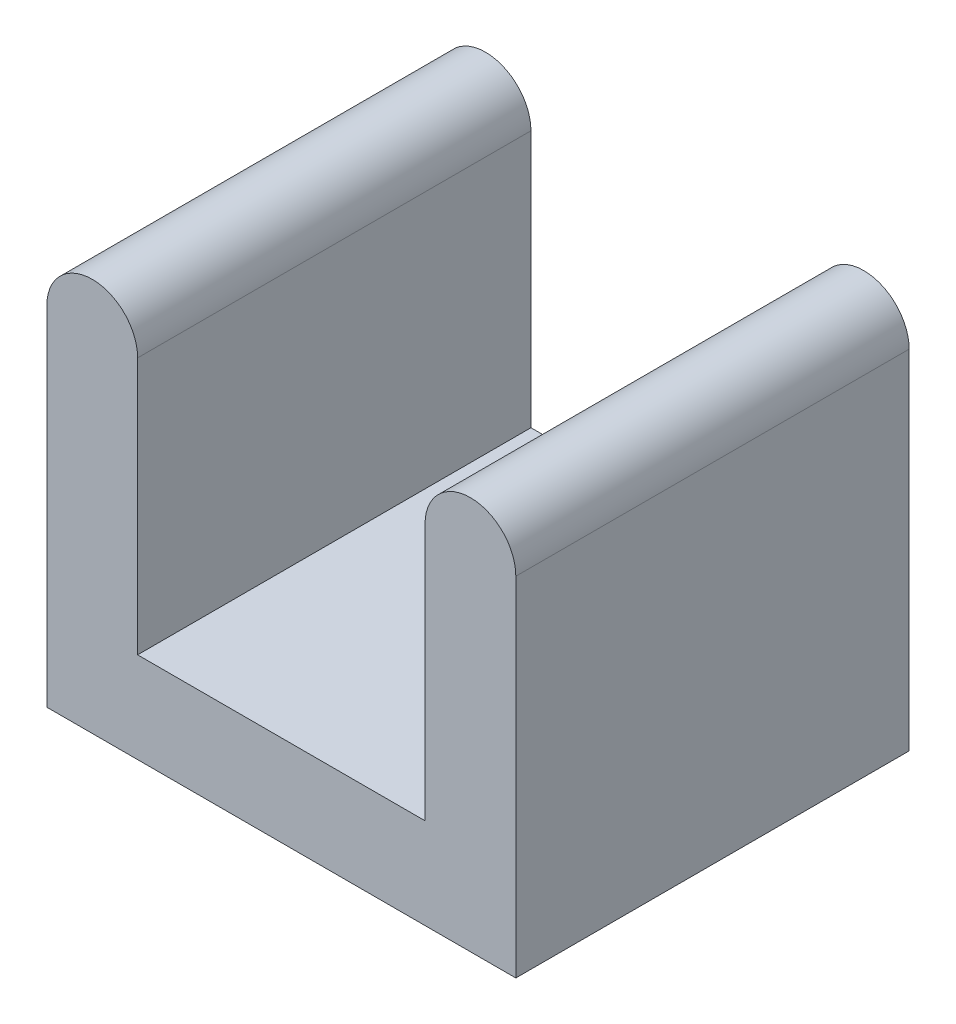
SolidWorks part; units mm, degrees
ref_plane "Front Plane" through (0, 0, 0) normal (0, 0, 1) x (1, 0, 0)
ref_plane "Top Plane" through (0, 0, 0) normal (0, 1, 0) x (1, 0, 0)
ref_plane "Right Plane" through (0, 0, 0) normal (1, 0, 0) x (0, 0, -1)
sketch "Sketch2" plane through (0, 0, 0) normal (0, 0, 1) x (1, 0, 0)
  line L0 (-29.0441, 29.9265) -> (-29.0441, 9.9265)
  line L1 (-29.0441, 9.9265) -> (-4.0441, 9.9265)
  line L2 (-4.0441, 9.9265) -> (-4.0441, 29.9265)
  line L3 (-32.0441, 29.9265) -> (-32.0441, 6.9265)
  line L4 (-32.0441, 6.9265) -> (-1.0441, 6.9265)
  line L5 (-1.0441, 6.9265) -> (-1.0441, 29.9265)
  line L6 (-26.0441, 29.9265) -> (-26.0441, 12.9265)
  line L7 (-26.0441, 12.9265) -> (-7.0441, 12.9265)
  line L8 (-7.0441, 12.9265) -> (-7.0441, 29.9265)
  arc A0 (-32.0441, 29.9265) -> (-26.0441, 29.9265) centre (-29.0441, 29.9265) cw
  arc A1 (-1.0441, 29.9265) -> (-7.0441, 29.9265) centre (-4.0441, 29.9265) ccw
  dimension "D1" = 25
  dimension "D2" = 20
  dimension "D3" = 20
extrude "Boss-Extrude5" add sketch "Sketch2" along normal blind 25 and the other way blind 1 contours L3 L4 L5 A1 L8 L7 L6 A0
